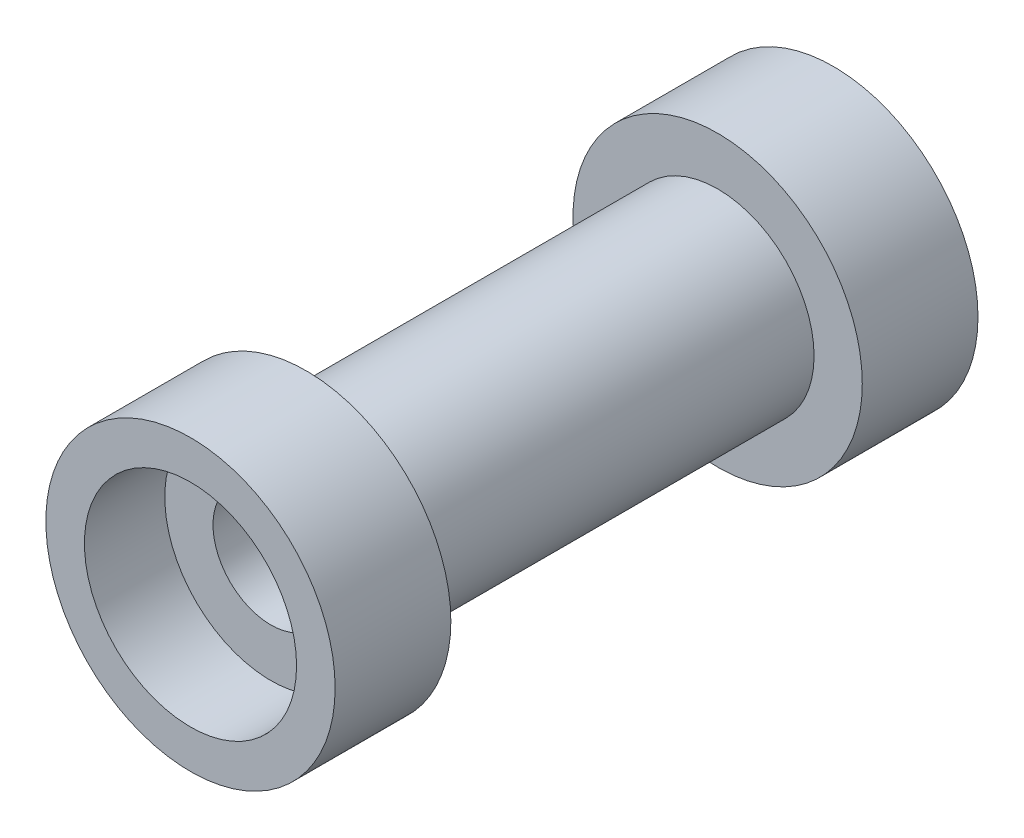
SolidWorks part; units mm, degrees
ref_plane "Front Plane" through (0, 0, 0) normal (0, 0, 1) x (1, 0, 0)
ref_plane "Top Plane" through (0, 0, 0) normal (0, 1, 0) x (1, 0, 0)
ref_plane "Right Plane" through (0, 0, 0) normal (1, 0, 0) x (0, 0, -1)
sketch "Sketch1" plane through (0, 0, 0) normal (0, 1, 0) x (1, 0, 0)
  line L0 (0, 0) -> (0, 20) construction
  line L1 (0, 0) -> (-9, 0) construction
  line L2 (-6, -12.8) -> (-6, 12.8)
  line L3 (-6, 12.8) -> (-9, 12.8)
  line L4 (-9, 12.8) -> (-9, 20)
  line L5 (-9, 20) -> (-6.6, 20)
  line L6 (-6.6, 20) -> (-6.6, 15)
  line L7 (-6.6, 15) -> (-3.6, 15)
  line L8 (-3.6, 15) -> (-3.6, -15)
  line L9 (-6.6, -15) -> (-3.6, -15)
  line L10 (-6.6, -20) -> (-6.6, -15)
  line L11 (-9, -20) -> (-6.6, -20)
  line L12 (-9, -12.8) -> (-9, -20)
  line L13 (-6, -12.8) -> (-9, -12.8)
  point P15 (-3.6, 0)
  point P20 (-6, 0)
  dimension "D1" = 6.6
  dimension "D2" = 5
  dimension "D3" = 9
  dimension "D4" = 3.6
  dimension "D5" = 7.2
  dimension "D6" = 12.8
  dimension "D7" = 6
  dimension "D8" = 40
  dimension "D9" = 2.2
revolve "Revolve1" add sketch "Sketch1" angle 360 about L0
